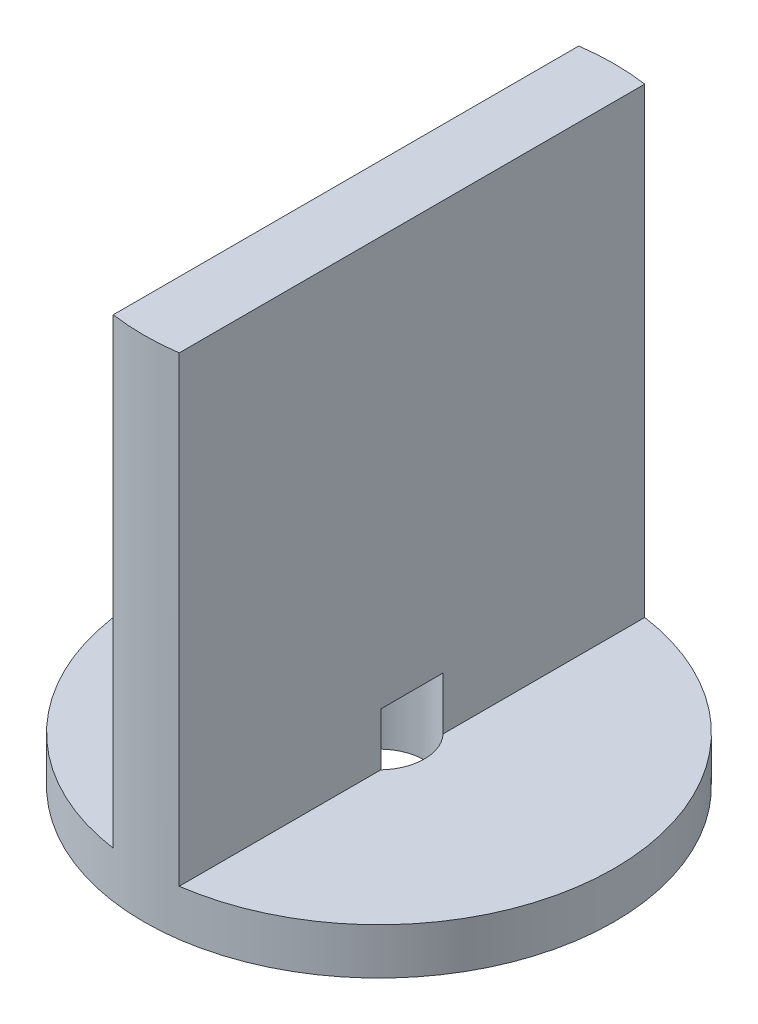
SolidWorks part; units mm, degrees
ref_plane "Front Plane" through (0, 0, 0) normal (0, 0, 1) x (1, 0, 0)
ref_plane "Top Plane" through (0, 0, 0) normal (0, 1, 0) x (1, 0, 0)
ref_plane "Right Plane" through (0, 0, 0) normal (1, 0, 0) x (0, 0, -1)
sketch "Sketch1" plane through (0, 0, 0) normal (0, 1, 0) x (1, 0, 0)
  circle A0 centre (0, 0) radius 36.195
  circle A1 centre (0, 0) radius 6.985
extrude "Boss-Extrude1" add sketch "Sketch1" along normal blind 7.112
sketch "Sketch4" plane through (0, 0, 0) normal (0, 1, 0) x (1, 0, 0)
  line L0 (-19.05, 0) -> (19.05, 0) construction
  line L1 (-3.9116, 0) -> (3.9116, 0) construction
  line L2 (0, -3.9116) -> (0, 3.9116) construction
  circle A0 centre (19.05, 0) radius 1.778
  circle A1 centre (-19.05, 0) radius 1.778
  point P9 (0, 0)
  dimension "D1" = 19.05
sketch "Sketch7" plane through (0, 7.112, 0) normal (0, 1, 0) x (1, 0, 0)
  line L0 (-5.08, 0) -> (5.08, 0) construction
  line L5 (5.08, -35.8367) -> (5.08, 35.8367)
  line L6 (0, -3.9116) -> (0, 3.9116) construction
  line L7 (-5.08, -35.8367) -> (-5.08, 35.8367)
  line L8 (-3.9116, 0) -> (3.9116, 0) construction
  circle A1 centre (0, 0) radius 36.195 construction
  point P0 (0, 0)
  point P11 (0, 0)
  circle M4 centre (0, 0) radius 36.195
  circle M5 centre (0, 0) radius 6.985
  dimension "D1" = 5.08
extrude "Boss-Extrude2" add sketch "Sketch7" along normal blind 71.12 contours L7 L5 M5 M4 | L7 L5 M4 M5 | L7 L0 L5 M5 | L0 L7 L5 M5
sketch "Sketch11" plane through (0, 7.112, 0) normal (0, -1, 0) x (1, 0, 0)
  line L0 (-5.08, 4.7941) -> (-5.08, -4.7941) construction
  line L1 (5.08, 4.7941) -> (5.08, -4.7941) construction
  line L2 (-5.08, 4.7941) -> (-5.08, -4.7941)
  line L3 (5.08, 4.7941) -> (5.08, -4.7941)
  circle A0 centre (0, 0) radius 6.985 construction
  circle A1 centre (0, 0) radius 6.985
  arc M1 (-5.08, -4.7941) -> (5.08, -4.7941) centre (0, 0) ccw
  line M2 (5.08, -4.7941) -> (5.08, 4.7941)
  arc M3 (5.08, 4.7941) -> (-5.08, 4.7941) centre (0, 0) ccw
  line M4 (-5.08, 4.7941) -> (-5.08, -4.7941)
extrude "Cut-Extrude1" cut sketch "Sketch11" against normal blind 8.128 contours M4 M1 M2 M3
hole_wizard "9/64 (0.14063) Diameter Hole2" positions "Sketch14" profile "Sketch15" hole size "9/64" standard "ANSI Inch"
sketch "Sketch14" plane through (0, 0, 0) normal (0, -1, 0) x (-1, 0, 0)
  point P0 (-19.05, 0)
  point P3 (19.05, 0)
sketch "Sketch15" plane through (19.05, 0, 0) normal (1, 0, 0) x (0, 0, -1)
  line L0 (0, 0) -> (0, 6.6611)
  line L1 (0, 6.6611) -> (1.786, 5.588)
  line L2 (1.786, 5.588) -> (1.786, 0)
  line L5 (1.786, 0) -> (0, 0)
  line L10 (0, 6.6611) -> (-1.786, 5.588) construction
  line L11 (0, -6.35) -> (0, 107.95) construction
  dimension "Hole Dia." = 3.572
  dimension "Hole Depth" = 5.588
  dimension "Drill Angle" = 118
